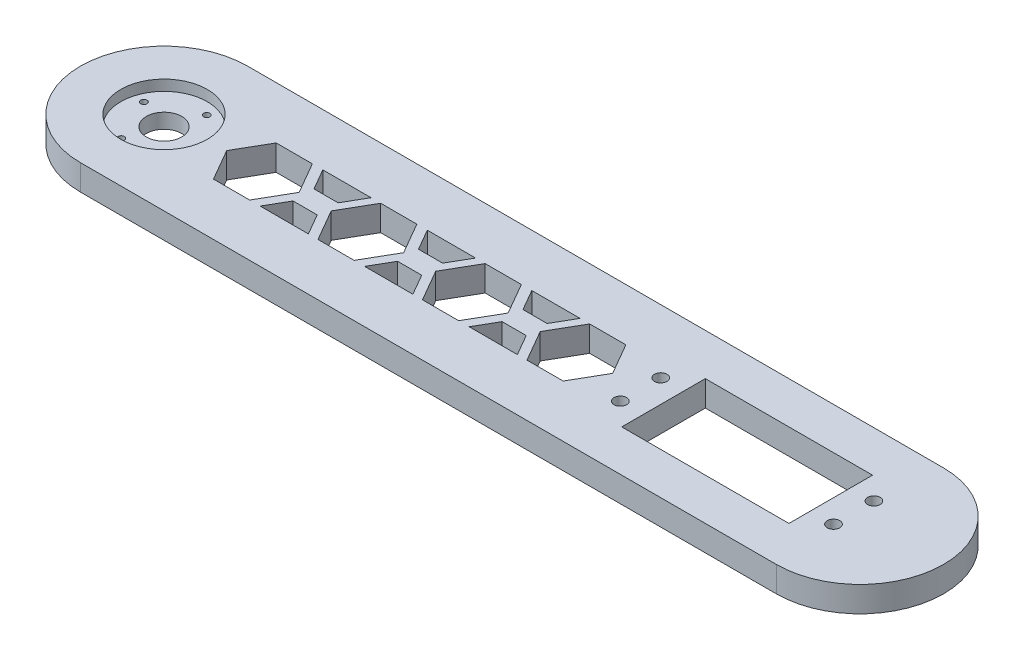
SolidWorks part; units mm, degrees
ref_plane "Front Plane" through (0, 0, 0) normal (0, 0, 1) x (1, 0, 0)
ref_plane "Top Plane" through (0, 0, 0) normal (0, 1, 0) x (1, 0, 0)
ref_plane "Right Plane" through (0, 0, 0) normal (1, 0, 0) x (0, 0, -1)
sketch "Sketch1" plane through (0, 0, 0) normal (0, 1, 0) x (1, 0, 0)
  line L0 (150, 20) -> (159.5, 20)
  line L1 (0, 20) -> (150, 20)
  line L2 (0, 20) -> (0, -20) construction
  line L3 (0, -20) -> (150, -20)
  line L4 (150, 20) -> (150, -20) construction
  line L5 (159.5, 20) -> (159.5, -20) construction
  line L6 (159.5, -20) -> (150, -20)
  line L7 (159.5, 20) -> (166.5, 20)
  line L8 (166.5, 20) -> (166.5, -20) construction
  line L9 (166.5, -20) -> (159.5, -20)
  line L10 (119.5, 10) -> (119.5, -10)
  line L11 (119.5, 10) -> (159.5, 10)
  line L13 (119.5, -10) -> (159.5, -10)
  line L14 (166.5, 10) -> (166.5, -10) construction
  line L15 (112.5, 13.2102) -> (112.5, -13.4878) construction
  line L16 (159.5, 10) -> (159.5, -10)
  circle A0 centre (0, 0) radius 4.25
  arc A1 (0, 20) -> (0, -20) centre (0, 0) ccw
  circle A2 centre (150, 0) radius 2.5 construction
  circle A3 centre (165, 4.825) radius 1.5
  circle A4 centre (165, -4.825) radius 1.5
  arc A5 (166.5, 20) -> (166.5, -20) centre (166.5, 0) cw
  circle A6 centre (114, 4.825) radius 1.5
  circle A7 centre (114, -4.825) radius 1.5
  point P31 (0, 0)
  dimension "D5" = 8.5
  dimension "D6" = 5
  dimension "D10" = 3
  dimension "D11" = 3
  dimension "D15" = 5.175
  dimension "D1" = 40
  dimension "D2" = 150
  dimension "D3" = 20
  dimension "D4" = 0
  dimension "D7" = 9.5
  dimension "D8" = 7
  dimension "D9" = 9.65
  dimension "D12" = 15.175
  dimension "D13" = 7
  dimension "D14" = 5.175
  dimension "D16" = 40
  dimension "D17" = 20
  dimension "D18" = 5.175
extrude "Boss-Extrude1" add sketch "Sketch1" along normal blind 6.1
sketch "Sketch2" plane through (0, 6.1, 0) normal (0, 1, 0) x (1, 0, 0)
  circle A0 centre (0, 0) radius 10.35
  dimension "D1" = 20.7
extrude "Cut-Extrude1" cut sketch "Sketch2" against normal blind 2.55
sketch "Sketch3" plane through (0, 3.55, 0) normal (0, 1, 0) x (1, 0, 0)
  line L0 (-7.525, 2.7156) -> (7.525, -2.7156) construction
  line L1 (2.7156, 7.525) -> (-2.7156, -7.525) construction
  circle A0 centre (-7.525, 2.7156) radius 0.75
  circle A1 centre (7.525, -2.7156) radius 0.75
  circle A2 centre (2.7156, 7.525) radius 0.75
  circle A3 centre (-2.7156, -7.525) radius 0.75
  point P9 (0, 0)
  point P12 (0, 0)
  dimension "D3" = 1.5
  dimension "D1" = 16
  dimension "D2" = 16
extrude "Cut-Extrude3" cut sketch "Sketch3" against normal up to surface (3.55 mm away) up to face at (165, 0, 6.325)
sketch "Sketch4" plane through (0, 6.1, 0) normal (0, 1, 0) x (1, 0, 0)
  line L0 (166.5, 20) -> (0, 20) construction
  line L1 (32.3205, 0) -> (27.9904, 7.5)
  line L2 (27.9904, 7.5) -> (19.3301, 7.5)
  line L3 (19.3301, 7.5) -> (15, 0)
  line L4 (15, 0) -> (19.3301, -7.5)
  line L5 (19.3301, -7.5) -> (27.9904, -7.5)
  line L6 (27.9904, -7.5) -> (32.3205, 0)
  line L7 (57.3205, 0) -> (52.9904, 7.5)
  line L8 (52.9904, 7.5) -> (44.3301, 7.5)
  line L9 (44.3301, 7.5) -> (40, 0)
  line L10 (40, 0) -> (44.3301, -7.5)
  line L11 (44.3301, -7.5) -> (52.9904, -7.5)
  line L12 (52.9904, -7.5) -> (57.3205, 0)
  line L13 (82.3205, 0) -> (77.9904, 7.5)
  line L14 (77.9904, 7.5) -> (69.3301, 7.5)
  line L15 (69.3301, 7.5) -> (65, 0)
  line L16 (65, 0) -> (69.3301, -7.5)
  line L17 (69.3301, -7.5) -> (77.9904, -7.5)
  line L18 (77.9904, -7.5) -> (82.3205, 0)
  line L19 (107.3205, 0) -> (102.9904, 7.5)
  line L20 (102.9904, 7.5) -> (94.3301, 7.5)
  line L21 (94.3301, 7.5) -> (90, 0)
  line L22 (90, 0) -> (94.3301, -7.5)
  line L23 (94.3301, -7.5) -> (102.9904, -7.5)
  line L24 (102.9904, -7.5) -> (107.3205, 0)
  line L25 (30.4904, 7.5) -> (42.0374, 7.5)
  line L29 (30.4904, 7.5) -> (33.3771, 2.5)
  line L30 (33.3771, 2.5) -> (39.1506, 2.5)
  line L31 (39.1506, 2.5) -> (42.0374, 7.5)
  line L32 (64.1506, 2.5) -> (67.0374, 7.5)
  line L33 (31.9372, 10.006) -> (30.4939, 7.506) [skipped]
  line L34 (42.0374, 7.5) -> (40.594, 10) [skipped]
  line L35 (39.1506, 12.5) -> (36.2639, 12.5) [skipped]
  line L36 (58.3771, 2.5) -> (64.1506, 2.5)
  line L37 (55.4904, 7.5) -> (58.3771, 2.5)
  line L38 (55.4904, 7.5) -> (67.0374, 7.5)
  line L39 (89.1506, 2.5) -> (92.0374, 7.5)
  line L40 (83.3771, 2.5) -> (89.1506, 2.5)
  line L41 (80.4904, 7.5) -> (83.3771, 2.5)
  line L42 (80.4904, 7.5) -> (92.0374, 7.5)
  line L43 (0, 0) -> (107.3205, 0) construction
  line L44 (30.4904, -7.5) -> (42.0374, -7.5)
  line L45 (30.4904, -7.5) -> (33.3771, -2.5)
  line L46 (33.3771, -2.5) -> (39.1506, -2.5)
  line L47 (39.1506, -2.5) -> (42.0374, -7.5)
  line L48 (55.4904, -7.5) -> (67.0374, -7.5)
  line L49 (64.1506, -2.5) -> (67.0374, -7.5)
  line L50 (58.3771, -2.5) -> (64.1506, -2.5)
  line L51 (55.4904, -7.5) -> (58.3771, -2.5)
  line L52 (80.4904, -7.5) -> (92.0374, -7.5)
  line L53 (89.1506, -2.5) -> (92.0374, -7.5)
  line L54 (83.3771, -2.5) -> (89.1506, -2.5)
  line L55 (80.4904, -7.5) -> (83.3771, -2.5)
  circle A0 centre (23.6603, 0) radius 7.5 construction
  circle A1 centre (0, 0) radius 10.35 construction
  circle A2 centre (36.2639, 7.5) radius 5 construction
  dimension "D1" = 15
  dimension "D2" = 12.5
  dimension "D3" = 15
  dimension "D5" = 5
  dimension "D6" = 2.5
  dimension "D4" = 4
  dimension "D7" = 3
  dimension "D8" = 3
extrude "Cut-Extrude4" cut sketch "Sketch4" against normal up to surface (6.1 mm away) up to face at (-7.525, 0, -1.9656)
